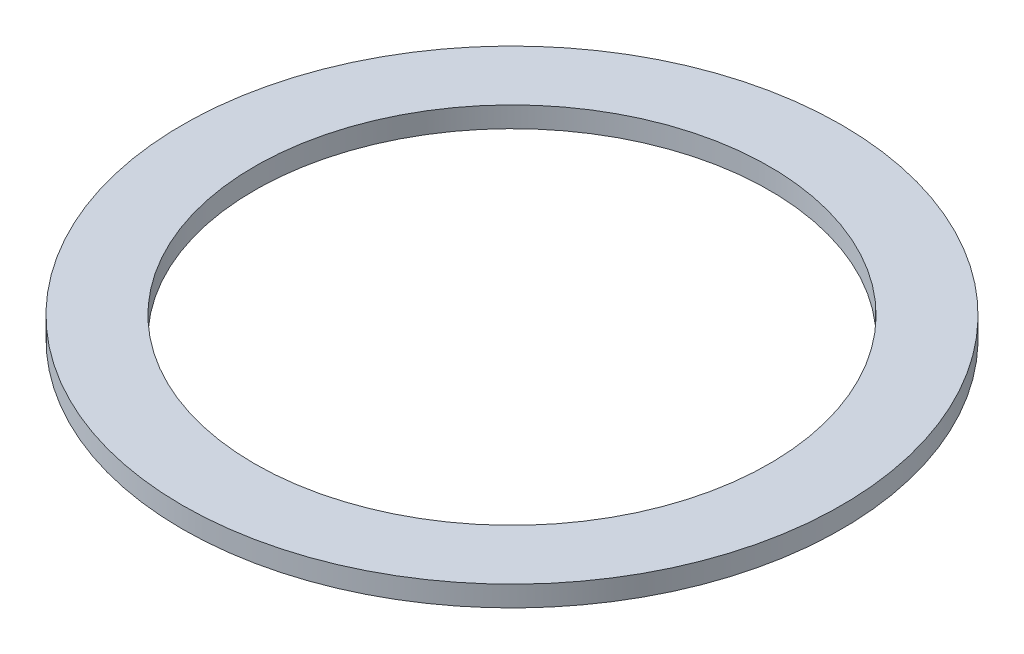
SolidWorks part; units mm, degrees
ref_plane "Спереди" through (0, 0, 0) normal (0, 0, 1) x (1, 0, 0)
ref_plane "Сверху" through (0, 0, 0) normal (0, 1, 0) x (1, 0, 0)
ref_plane "Справа" through (0, 0, 0) normal (1, 0, 0) x (0, 0, -1)
sketch "Эскиз1" plane through (0, 0, 0) normal (0, 1, 0) x (1, 0, 0)
  circle A0 centre (0, 0) radius 16
  circle A1 centre (0, 0) radius 12.5
  dimension "D1" = 32
  dimension "D2" = 25
extrude "Бобышка-Вытянуть1" add sketch "Эскиз1" along normal blind 1
